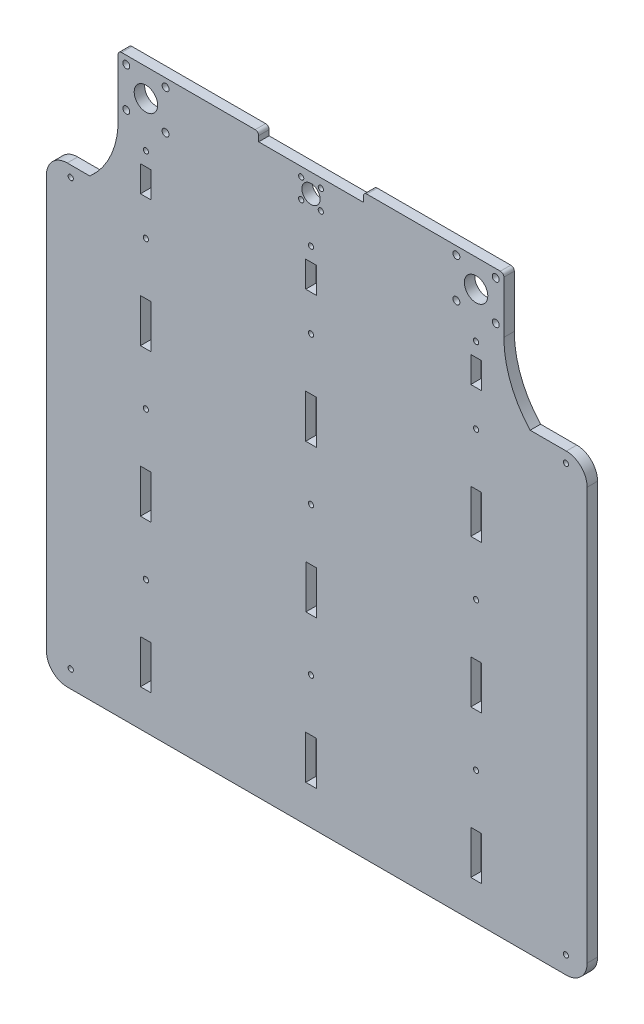
SolidWorks part; units mm, degrees
ref_plane "Alzado" through (0, 0, 0) normal (0, 0, 1) x (1, 0, 0)
ref_plane "Planta" through (0, 0, 0) normal (0, 1, 0) x (1, 0, 0)
ref_plane "Vista lateral" through (0, 0, 0) normal (1, 0, 0) x (0, 0, -1)
sketch "Croquis1" plane through (0, 0, 0) normal (0, 0, 1) x (1, 0, 0)
  line L0 (32.1154, 16) -> (87.6356, 16)
  line L1 (-109, 16) -> (-87.6356, 16)
  line L2 (-111, 14) -> (-111, -16)
  line L3 (-135.2776, -315.9124) -> (-119.3643, -315.9124)
  line L4 (-87.6356, 16) -> (-44.6644, 16)
  line L5 (30.1154, 14) -> (30.1154, 10.91)
  line L6 (0, 0) -> (0, 78.8056) construction
  line L7 (30.1154, 10.91) -> (-30.1154, 10.91)
  line L8 (-111, 0) -> (-111, -16)
  line L9 (-111, -16) -> (-111, 16)
  line L10 (-44.6644, 16) -> (-32.1154, 16)
  line L11 (-119.3643, -315.9124) -> (119.3644, -315.9124)
  line L12 (111, 14) -> (111, -16)
  line L13 (109, 16) -> (87.6356, 16)
  line L14 (-30.1154, 14) -> (-30.1154, 10.91)
  line L15 (-8.3, -8.3) -> (8.3, 8.3) construction
  line L16 (-127.2776, -54.7017) -> (126.134, -54.7017) construction
  line L17 (-95, 0) -> (-95, -315.9124) construction
  line L18 (119.3644, -315.9124) -> (130.2951, -315.9124)
  line L19 (-8.3, 8.3) -> (8.3, -8.3) construction
  line L20 (-127.2776, -54.7017) -> (-135.2776, -54.7017)
  line L21 (-111, 16) -> (-79, -16) construction
  line L22 (-111, -16) -> (-79, 16) construction
  line L23 (-135.2776, -54.7017) -> (-140.2776, -54.7017)
  line L24 (-138.2776, -60.9124) -> (-136.7776, -60.9124) construction
  line L25 (-111, -16) -> (-79, -16) construction
  line L26 (-135.2776, -315.9124) -> (-140.2776, -315.9124)
  line L27 (-152.2776, -66.7017) -> (-152.2776, -303.9124)
  line L28 (-79, -16) -> (111, -16) construction
  line L29 (130.2951, -315.9124) -> (146.9429, -315.9124)
  line L30 (158.9429, -70.771) -> (158.9429, -303.9124)
  line L31 (145.2224, -60.9124) -> (146.7224, -60.9124) construction
  line L32 (126.134, -54.7017) -> (146.9429, -54.7017)
  line L33 (0, 0) -> (0.0001, -316) construction
  line L34 (95, 0) -> (95, -316) construction
  line L35 (158.9429, -66.7017) -> (158.9429, -70.771)
  line L36 (-98.15, -184.7017) -> (-91.95, -184.7017)
  line L37 (-98.15, -34) -> (-91.95, -34)
  line L38 (-98.15, -34) -> (-98.15, -49)
  line L39 (-98.15, -49) -> (-91.95, -49)
  line L40 (-91.95, -34) -> (-91.95, -49)
  line L41 (-98.15, -99.7017) -> (-91.95, -99.7017)
  line L42 (-98.15, -99.7017) -> (-98.15, -124.7017)
  line L43 (-98.15, -124.7017) -> (-91.95, -124.7017)
  line L44 (-91.95, -99.7017) -> (-91.95, -124.7017)
  line L45 (-98.15, -184.7017) -> (-98.15, -209.7017)
  line L46 (-98.15, -209.7017) -> (-91.95, -209.7017)
  line L47 (-91.95, -184.7017) -> (-91.95, -209.7017)
  line L48 (-98.15, -269.7017) -> (-91.95, -269.7017)
  line L49 (-98.15, -269.7017) -> (-98.15, -294.7017)
  line L50 (-98.15, -294.7017) -> (-91.95, -294.7017)
  line L51 (-91.95, -269.7017) -> (-91.95, -294.7017)
  line L52 (-98.15, -99.7017) -> (-98.15, -184.7017) construction
  line L53 (98.15, -99.7017) -> (98.1501, -184.7017) construction
  line L54 (95, 0) -> (95.0001, -315.9124) construction
  line L55 (127.2776, -54.7016) -> (-126.134, -54.7018) construction
  line L56 (91.9501, -269.7017) -> (91.9501, -294.7017)
  line L57 (98.1501, -294.7017) -> (91.9501, -294.7017)
  line L58 (98.1501, -269.7017) -> (98.1501, -294.7017)
  line L59 (98.1501, -269.7017) -> (91.9501, -269.7017)
  line L60 (91.9501, -184.7017) -> (91.9501, -209.7017)
  line L61 (98.1501, -209.7017) -> (91.9501, -209.7017)
  line L62 (98.1501, -184.7017) -> (98.1501, -209.7017)
  line L63 (91.95, -99.7017) -> (91.9501, -124.7017)
  line L64 (98.1501, -124.7017) -> (91.9501, -124.7017)
  line L65 (98.15, -99.7017) -> (98.1501, -124.7017)
  line L66 (98.15, -99.7017) -> (91.95, -99.7017)
  line L67 (91.95, -34) -> (91.95, -49)
  line L68 (98.15, -49) -> (91.95, -49)
  line L69 (98.15, -34) -> (98.15, -49)
  line L70 (98.15, -34) -> (91.95, -34)
  line L71 (98.1501, -184.7017) -> (91.9501, -184.7017)
  line L72 (3.15, -99.7892) -> (3.1501, -184.7892) construction
  line L73 (-3.0499, -269.7892) -> (-3.0499, -294.7892)
  line L74 (3.0501, -294.7892) -> (-3.0499, -294.7892)
  line L75 (3.0501, -269.7892) -> (3.0501, -294.7892)
  line L76 (3.0501, -269.7892) -> (-3.0499, -269.7892)
  line L77 (-2.9499, -184.7892) -> (-2.9499, -209.7892)
  line L78 (3.1501, -209.7892) -> (-2.9499, -209.7892)
  line L79 (3.1501, -184.7892) -> (3.1501, -209.7892)
  line L80 (-3.05, -99.7892) -> (-3.05, -124.7892)
  line L81 (3.15, -124.7892) -> (-3.05, -124.7892)
  line L82 (3.15, -99.7892) -> (3.15, -124.7892)
  line L83 (3.15, -99.7892) -> (-3.05, -99.7892)
  line L84 (-3.05, -34) -> (-3.05, -49)
  line L85 (3.15, -49) -> (-3.05, -49)
  line L86 (3.15, -34) -> (3.15, -49)
  line L87 (3.15, -34) -> (-3.05, -34)
  line L88 (3.1501, -184.7892) -> (-2.9499, -184.7892)
  line L89 (95, -26) -> (-95, -26) construction
  circle A0 centre (0, 0) radius 5.25
  circle A1 centre (-95, 0) radius 6.75
  circle A2 centre (95, 0) radius 6.75
  circle A3 centre (146.7224, -60.9124) radius 1.5
  circle A4 centre (-83.6863, 11.3137) radius 2
  circle A5 centre (-106.3137, 11.3137) radius 2
  circle A6 centre (-83.6863, -11.3137) radius 2
  circle A7 centre (-106.3137, -11.3137) radius 2
  circle A8 centre (106.3137, -11.3137) radius 2
  circle A9 centre (83.6863, -11.3137) radius 2
  circle A10 centre (83.6863, 11.3137) radius 2
  arc A11 (-111, -16) -> (-127.2776, -54.7017) centre (-158.9474, -18.6077) cw
  arc A12 (111, -16) -> (126.134, -54.7017) centre (168.0523, -16) ccw
  arc A13 (-140.2776, -315.9124) -> (-152.2776, -303.9124) centre (-140.2776, -303.9124) cw
  arc A14 (158.9429, -303.9124) -> (146.9429, -315.9124) centre (146.9429, -303.9124) cw
  arc A15 (158.9429, -66.7017) -> (146.9429, -54.7017) centre (146.9429, -66.7017) ccw
  circle A16 centre (5.6569, 5.6569) radius 1.5
  circle A17 centre (-5.6569, 5.6569) radius 1.5
  circle A18 centre (-5.6569, -5.6569) radius 1.5
  circle A19 centre (5.6569, -5.6569) radius 1.5
  arc A20 (-140.2776, -54.7017) -> (-152.2776, -66.7017) centre (-140.2776, -66.7017) ccw
  circle A21 centre (146.7224, -305.9124) radius 1.5
  circle A22 centre (-138.2776, -305.9124) radius 1.5
  circle A23 centre (-138.2776, -60.9124) radius 1.5
  circle A24 centre (-95, -26) radius 1.5
  circle A25 centre (-95, -69.7017) radius 1.5
  circle A26 centre (-95, -154.7017) radius 1.5
  circle A27 centre (-95, -239.7017) radius 1.5
  circle A28 centre (95.0001, -239.7017) radius 1.5
  arc A29 (109, 16) -> (111, 14) centre (109, 14) cw
  arc A30 (-111, 14) -> (-109, 16) centre (-109, 14) cw
  circle A31 centre (95.0001, -154.7017) radius 1.5
  circle A32 centre (95, -69.7017) radius 1.5
  circle A33 centre (95, -26) radius 1.5
  circle A34 centre (0.0001, -239.7892) radius 1.5
  arc A35 (-32.1154, 16) -> (-30.1154, 14) centre (-32.1154, 14) cw
  circle A36 centre (0.0001, -154.7892) radius 1.5
  circle A37 centre (106.3137, 11.3137) radius 2
  arc A38 (30.1154, 14) -> (32.1154, 16) centre (32.1154, 14) cw
  circle A39 centre (0, -69.7892) radius 1.5
  circle A40 centre (0.0046, -26) radius 1.5
  point P71 (0, 16)
  point P98 (111, 16)
  point P101 (-111, 16)
  point P106 (30.1154, 16)
  point P108 (-147.2776, -54.7017)
  dimension "D3" = 285
  dimension "D4" = 12
  dimension "D5" = 10.5
  dimension "D6" = 14
  dimension "D7" = 285
  dimension "D8" = 13.5
  dimension "D9" = 245
  dimension "D10" = 4
  dimension "D11" = 222
  dimension "D12" = 16
  dimension "D13" = 10
  dimension "D16" = 190
  dimension "D2" = 13.5
  dimension "D18" = 14
  dimension "D21" = 4
  dimension "D19" = 4
  dimension "D20" = 4
  dimension "D22" = 2
  dimension "D24" = 12
  dimension "D25" = 12
  dimension "D34" = 15
  dimension "D14" = 16
  dimension "D15" = 6.2
  dimension "D17" = 95
  dimension "D23" = 20
  dimension "D26" = 5.2532
  dimension "D27" = 5.2532
  dimension "D28" = 11.3137
  dimension "D29" = 11.3137
  dimension "D30" = 11.3137
  dimension "D31" = 11.3137
  dimension "D32" = 15
  dimension "D33" = 8
  dimension "D35" = 25
  dimension "D36" = 30
  dimension "D38" = 85
  dimension "D39" = 10
  dimension "D40" = 10
  dimension "D41" = 20.7017
  dimension "D42" = 6.2
  dimension "D43" = 6.2
  dimension "D44" = 6.2
  dimension "D37" = 3
extrude "Saliente-Extruir1" add sketch "Croquis1" along normal blind 6
